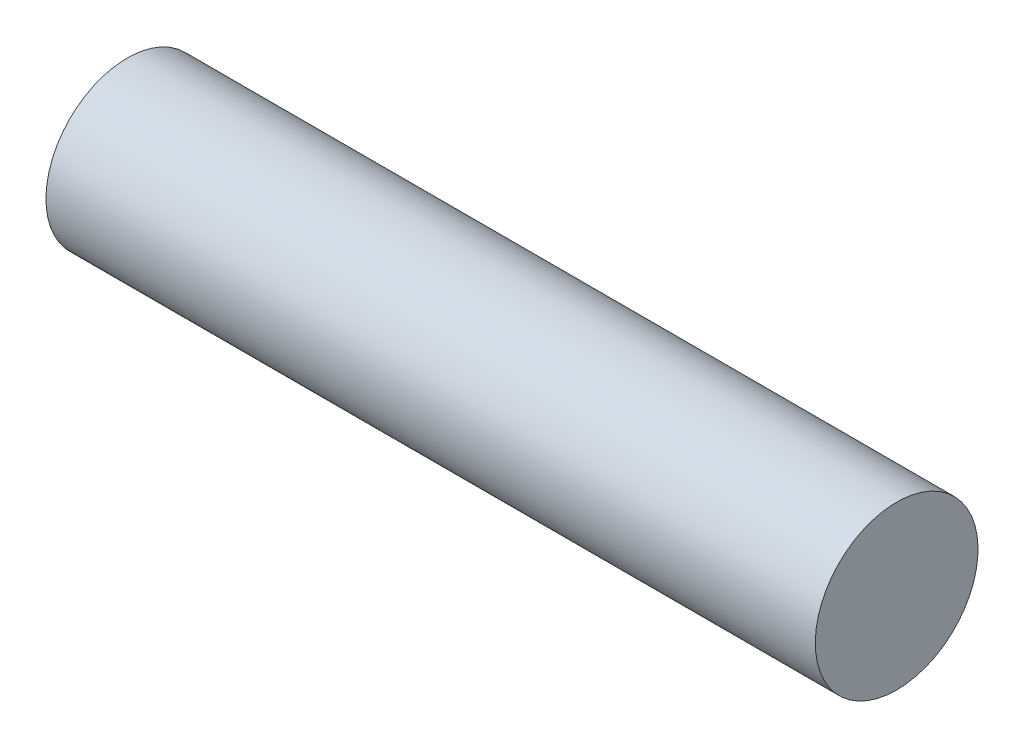
SolidWorks part; units mm, degrees
ref_plane "Front Plane" through (0, 0, 0) normal (0, 0, 1) x (1, 0, 0)
ref_plane "Top Plane" through (0, 0, 0) normal (0, 1, 0) x (1, 0, 0)
ref_plane "Right Plane" through (0, 0, 0) normal (1, 0, 0) x (0, 0, -1)
sketch "Sketch1" plane through (0, 0, 0) normal (0, 0, 1) x (1, 0, 0)
  line L0 (-26, 0) -> (26, 0)
  line L1 (26, 0) -> (26, 5.5)
  line L2 (26, 5.5) -> (-26, 5.5)
  line L3 (-26, 5.5) -> (-26, 0)
  point P4 (0, 0)
  dimension "D1" = 52
  dimension "D2" = 5.5
revolve "Revolve1" add sketch "Sketch1" angle 360 about L0
